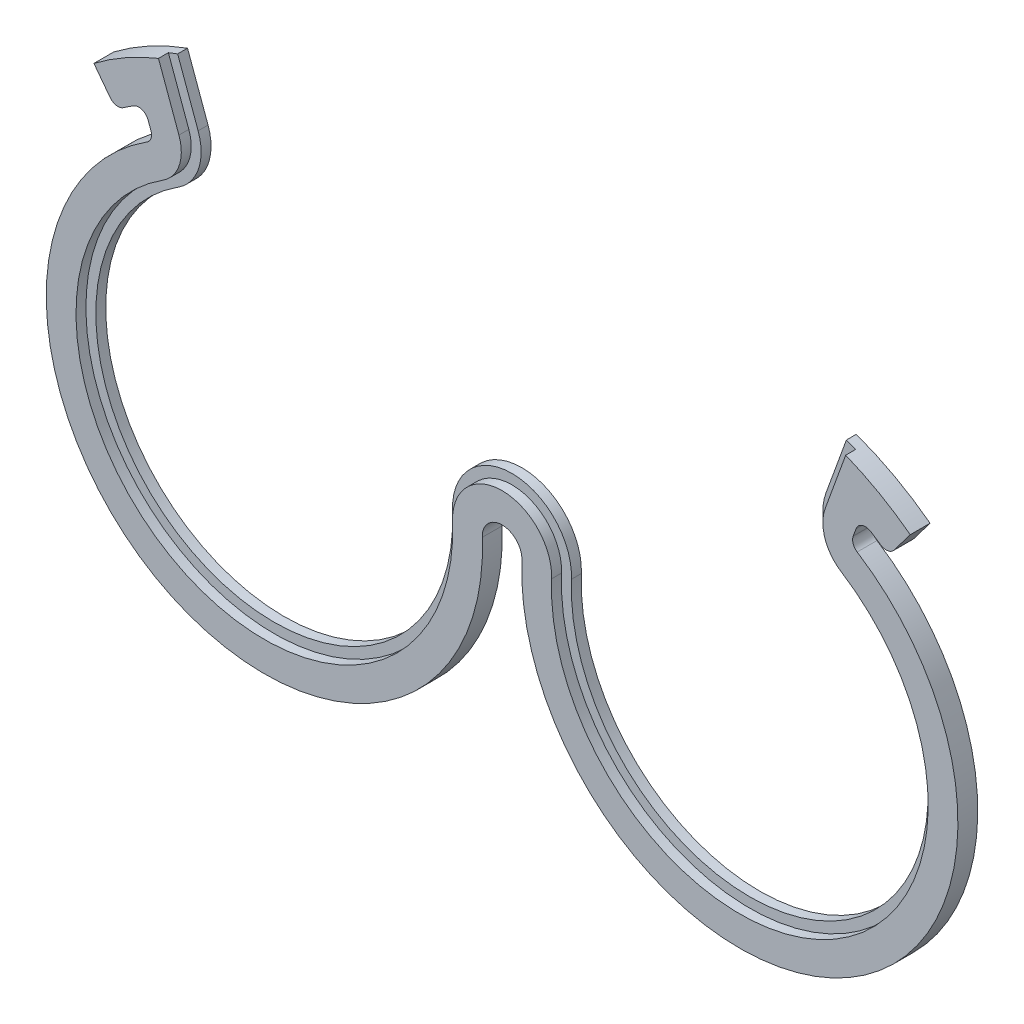
SolidWorks part; units mm, degrees
ref_plane "Plan1" through (0, 0, 0) normal (0, 0, 1) x (1, 0, 0)
ref_plane "Plan2" through (0, 0, 0) normal (0, 1, 0) x (1, 0, 0)
ref_plane "Plan3" through (0, 0, 0) normal (1, 0, 0) x (0, 0, -1)
sketch "Esquisse1" plane through (0, 0, 0) normal (0, 0, 1) x (1, 0, 0)
  line L0 (33.7476, 26.7812) -> (31.6783, 21.096)
  line L1 (35.4371, 19.728) -> (35.724, 20.5161)
  line L3 (0.0208, 7) -> (0.0208, 3)
  line L5 (39.5627, 20.5777) -> (41.1914, 22.7312)
  arc A0 (6.0156, 0.75) -> (33.6862, 15.1716) centre (24, 0) ccw
  arc A1 (2.0191, 0.9167) -> (35.8387, 18.5431) centre (24, 0) ccw
  arc A2 (38.1933, 20.3605) -> (37.1953, 21.021) centre (24, 0) ccw
  arc A3 (6.0156, 0.75) -> (0.0208, 7) centre (0.0208, 1) ccw
  arc A4 (2.0191, 0.9167) -> (0.0208, 3) centre (0.0208, 1) ccw
  arc A6 (33.6862, 15.1716) -> (31.6783, 21.096) centre (36.3768, 19.3859) cw
  arc A7 (35.8387, 18.5431) -> (35.4371, 19.728) centre (36.3768, 19.3859) cw
  arc A8 (37.1953, 21.021) -> (35.724, 20.5161) centre (36.6637, 20.1741) ccw
  arc A10 (38.1933, 20.3605) -> (39.5627, 20.5777) centre (38.7652, 21.1809) ccw
  arc A11 (41.1914, 22.7312) -> (33.7476, 26.7812) centre (24, 0) ccw
  dimension "D1" = 6
  dimension "D3" = 5
  dimension "D4" = 1
  dimension "D5" = 1
  dimension "D7" = 57
  dimension "D2" = 4
extrude "Base-Extrusion" add sketch "Esquisse1" along normal blind 2
sketch "Esquisse2" plane through (0, 0, 2) normal (0, 0, 1) x (1, 0, 0)
  line L0 (33.7476, 26.7812) -> (31.6783, 21.096)
  line L1 (0.0208, 6) -> (0.0208, 7)
  line L2 (34.6813, 26.4227) -> (32.618, 20.754)
  arc A0 (6.0156, 0.75) -> (33.6862, 15.1716) centre (24, 0) ccw
  arc A1 (34.2243, 16.0145) -> (32.618, 20.754) centre (36.3768, 19.3859) cw
  arc A2 (6.0156, 0.75) -> (0.0208, 7) centre (0.0208, 1) ccw
  arc A3 (5.0165, 0.7917) -> (0.0208, 6) centre (0.0208, 1) ccw
  arc A4 (5.0165, 0.7917) -> (34.2243, 16.0145) centre (24, 0) ccw
  arc A5 (33.6862, 15.1716) -> (31.6783, 21.096) centre (36.3768, 19.3859) cw
  arc A6 (34.6813, 26.4227) -> (33.7476, 26.7812) centre (24, 0) ccw
  dimension "D3" = 4
  dimension "D4" = 5
  dimension "D1" = 1
extrude "Enlèv. mat.-Extru.1" cut sketch "Esquisse2" against normal blind 1
mirror "Bossage-Symétrie1"
